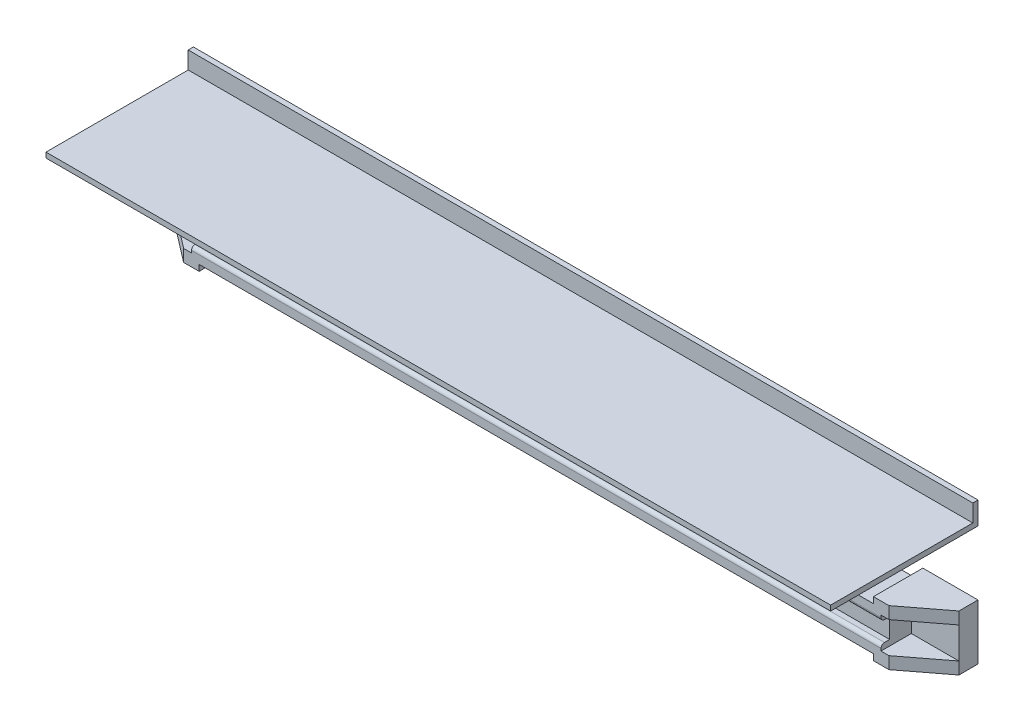
SolidWorks part; units mm, degrees
ref_plane "Front Plane" through (0, 0, 0) normal (0, 0, 1) x (1, 0, 0)
ref_plane "Top Plane" through (0, 0, 0) normal (0, 1, 0) x (1, 0, 0)
ref_plane "Right Plane" through (0, 0, 0) normal (1, 0, 0) x (0, 0, -1)
sketch "Sketch1" plane through (0, 0, 0) normal (0, 0, 1) x (1, 0, 0)
  line L1 (0, 0) -> (400, 0)
  line L2 (0, 0) -> (0, 25)
  line L3 (0, 25) -> (400, 25)
  line L4 (400, 0) -> (400, 25)
  dimension "D1" = 400
  dimension "D2" = 25
extrude "Boss-Extrude1" add sketch "Sketch1" along normal blind 25
sketch "Sketch2" plane through (0, 0, 25) normal (0, 0, 1) x (1, 0, 0)
  line L0 (6.8, 18.2) -> (6.8, 6.8)
  line L1 (6.8, 6.8) -> (393.2, 6.8)
  line L2 (393.2, 6.8) -> (393.2, 18.2)
  line L3 (393.2, 18.2) -> (6.8, 18.2)
  line L4 (0, 25) -> (0, 0)
  line L5 (0, 0) -> (400, 0)
  line L6 (400, 0) -> (400, 25)
  line L7 (400, 25) -> (0, 25)
  line L8 (0, 25) -> (0, 0)
  line L9 (0, 0) -> (400, 0)
  line L10 (400, 0) -> (400, 25)
  line L11 (400, 25) -> (0, 25)
  dimension "D1" = 0
  dimension "D2" = 6.8
extrude "Cut-Extrude2" cut sketch "Sketch2" against normal blind 5 contours L0 L1 L2 L3
ref_plane "Plane1" through (200, 0, 0) normal (1, 0, 0) x (0, 0, -1)
sketch "Sketch4" plane through (6.8, 0, 0) normal (1, 0, 0) x (0, 0, -1)
  line L4 (0, 0) -> (0, 25)
  line L5 (-25, 0) -> (0, 0)
  line L6 (-25, 25) -> (-25, 0)
  line L7 (0, 25) -> (-25, 25)
  line L8 (0, 0) -> (0, 25)
  line L9 (-25, 0) -> (0, 0)
  line L10 (-25, 25) -> (-25, 0)
  line L11 (0, 25) -> (-25, 25)
  line L16 (3.5, -3.5) -> (3.5, 28.5)
  line L17 (-28.5, -3.5) -> (3.5, -3.5)
  line L18 (-28.5, 28.5) -> (-28.5, -3.5)
  line L19 (3.5, 28.5) -> (-28.5, 28.5)
  line L20 (3.5, -3.5) -> (3.5, 28.5)
  line L21 (-28.5, -3.5) -> (3.5, -3.5)
  line L22 (-28.5, 28.5) -> (-28.5, -3.5)
  line L23 (3.5, 28.5) -> (-28.5, 28.5)
  dimension "D1" = 0
  dimension "D2" = 3.5
extrude "Boss-Extrude2" add sketch "Sketch4" against normal up to surface (6.8 mm away) separate body up to face at (0, 12.5, 12.5)
sketch "Sketch5" plane through (0, 0, 0) normal (-1, 0, 0) x (0, 0, 1)
  line L4 (-3.5, -3.5) -> (28.5, -3.5) construction
  line L5 (28.5, -3.5) -> (28.5, 28.5) construction
  line L6 (28.5, 28.5) -> (-3.5, 28.5) construction
  line L7 (-3.5, 28.5) -> (-3.5, -3.5) construction
  line L12 (-3.5, -3.5) -> (28.5, -3.5)
  line L13 (28.5, -3.5) -> (28.5, 28.5)
  line L14 (28.5, 28.5) -> (-3.5, 28.5)
  line L15 (-3.5, 28.5) -> (-3.5, -3.5)
extrude "Boss-Extrude3" add sketch "Sketch5" along normal blind 25
sketch "Sketch6" plane through (0, 0, 28.5) normal (0, 0, 1) x (1, 0, 0)
  line L0 (-25, -3.5) -> (-25, 28.5) construction
  line L1 (-25, 21.5) -> (2.4481, 21.5)
  line L2 (-25, 21.5) -> (-25, 3.5)
  line L3 (-25, 3.5) -> (2.4481, 3.5)
  line L4 (2.4481, 21.5) -> (2.4481, 3.5)
  line L5 (6.8, 12.5) -> (4.7005, 12.5) construction
  line L6 (6.8, 28.5) -> (6.8, -3.5) construction
  line L7 (-25, -3.5) -> (6.8, -3.5) construction
  dimension "D1" = 18
  dimension "D2" = 7
extrude "Cut-Extrude3" cut sketch "Sketch6" against normal blind 21
sketch "Sketch7" plane through (0, -3.5, 0) normal (0, -1, 0) x (1, 0, 0)
  line L0 (-25, 28.5) -> (2.4481, 28.5) construction
  line L3 (-25, 7.5) -> (-25, 28.5) construction
  line L6 (6.8, 28.5) -> (-25, 28.5) construction
  line L7 (-25, 28.5) -> (-25, -3.5) construction
  line L9 (-25, 28.5) -> (2.4481, 28.5)
  line L12 (-25, 7.5) -> (-25, 28.5)
  line L15 (2.4481, 28.5) -> (-25, 28.5)
  line L16 (-25, 28.5) -> (-25, 7.5)
  line L18 (2.4481, 28.5) -> (-25, 7.5)
  line M3 (6.8, 28.5) -> (-25, 28.5)
  line M4 (-25, 28.5) -> (-25, -3.5)
extrude "Cut-Extrude4" cut sketch "Sketch7" against normal blind 43 contours L18 M3 M4
sketch "Sketch8" plane through (2.4481, 0, 0) normal (-1, 0, 0) x (0, 0, 1)
  line L0 (20, 6.8) -> (25, 6.8) construction
  line L1 (20, 18.2) -> (25, 18.2) construction
  line L2 (25, 25) -> (25, 18.2) construction
  line L3 (20, 18.2) -> (20, 6.8) construction
  line L4 (25, 6.8) -> (25, 0) construction
  line L5 (20, 6.8) -> (23, 6.8)
  line L6 (20, 18.2) -> (23, 18.2)
  line L7 (25, 30.7464) -> (25, 20.2)
  line L8 (20, 18.2) -> (20, 6.8)
  line L9 (25, 4.8) -> (25, -5.0208)
  line L10 (25, 30.7464) -> (31.9916, 30.7464)
  line L11 (31.9916, 30.7464) -> (31.9916, -5.0208)
  line L12 (31.9916, -5.0208) -> (25, -5.0208)
  arc A0 (23, 6.8) -> (25, 4.8) centre (23, 4.8) cw
  arc A1 (23, 18.2) -> (25, 20.2) centre (23, 20.2) ccw
  dimension "D1" = 2
extrude "Cut-Extrude5" cut sketch "Sketch8" against normal blind 413 and the other way blind 43
ref_plane "Plane2" through (201.2241, 0, 0) normal (1, 0, 0) x (0, 0, -1)
mirror "Mirror6" about plane through (201.2241, 0, 0) normal (1, 0, 0) of bodies 113 114
sketch "Sketch9" plane through (427.4481, 0, 0) normal (1, 0, 0) x (0, 0, -1)
  line L0 (3.5, 78.4381) -> (3.5, 65.4381)
  line L1 (3.5, 65.4381) -> (-81.5, 65.4381)
  line L2 (-81.5, 65.4381) -> (-81.5, 68.4381)
  line L3 (-81.5, 68.4381) -> (0.5, 68.4381)
  line L4 (0.5, 68.4381) -> (0.5, 78.4381)
  line L5 (0.5, 78.4381) -> (3.5, 78.4381)
  line L6 (3.5, -279.5619) -> (3.5, 90.4381) construction
  line L7 (43.5, 90.4381) -> (3.5, 90.4381) construction
  line L8 (-81.5, 68.4381) -> (-46.5, 68.4381) construction
  line L9 (-81.5, 36.0519) -> (-81.5, 68.4381) construction
  dimension "D1" = 3
  dimension "D2" = 3
  dimension "D4" = 12
extrude "Boss-Extrude4" add sketch "Sketch9" against normal up to surface (452.4481 mm away) separate body up to face at (-25, 12.5, 3.8333)
